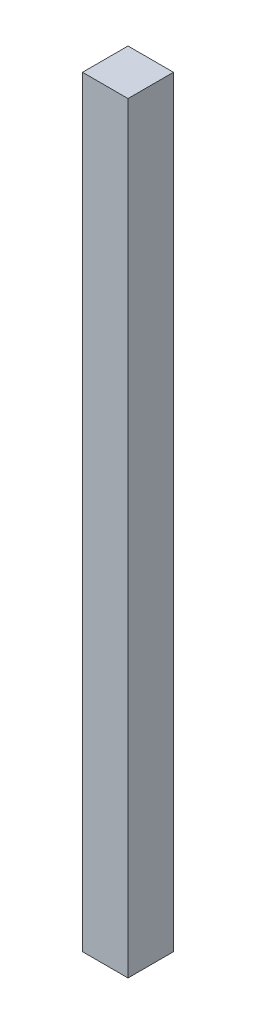
SolidWorks part; units mm, degrees
ref_plane "Front Plane" through (0, 0, 0) normal (0, 0, 1) x (1, 0, 0)
ref_plane "Top Plane" through (0, 0, 0) normal (0, 1, 0) x (1, 0, 0)
ref_plane "Right Plane" through (0, 0, 0) normal (1, 0, 0) x (0, 0, -1)
sketch "Sketch1" plane through (0, 0, 0) normal (0, 1, 0) x (1, 0, 0)
  line L1 (-25.4, -25.4) -> (25.4, -25.4)
  line L2 (-25.4, -25.4) -> (-25.4, 25.4)
  line L3 (-25.4, 25.4) -> (25.4, 25.4)
  line L4 (25.4, -25.4) -> (25.4, 25.4)
  line L5 (-25.4, -25.4) -> (25.4, 25.4) construction
  line L6 (-25.4, 25.4) -> (25.4, -25.4) construction
  point P0 (0, 0)
  dimension "D1" = 50.8
extrude "Boss-Extrude1" add sketch "Sketch1" along normal blind 850.392
